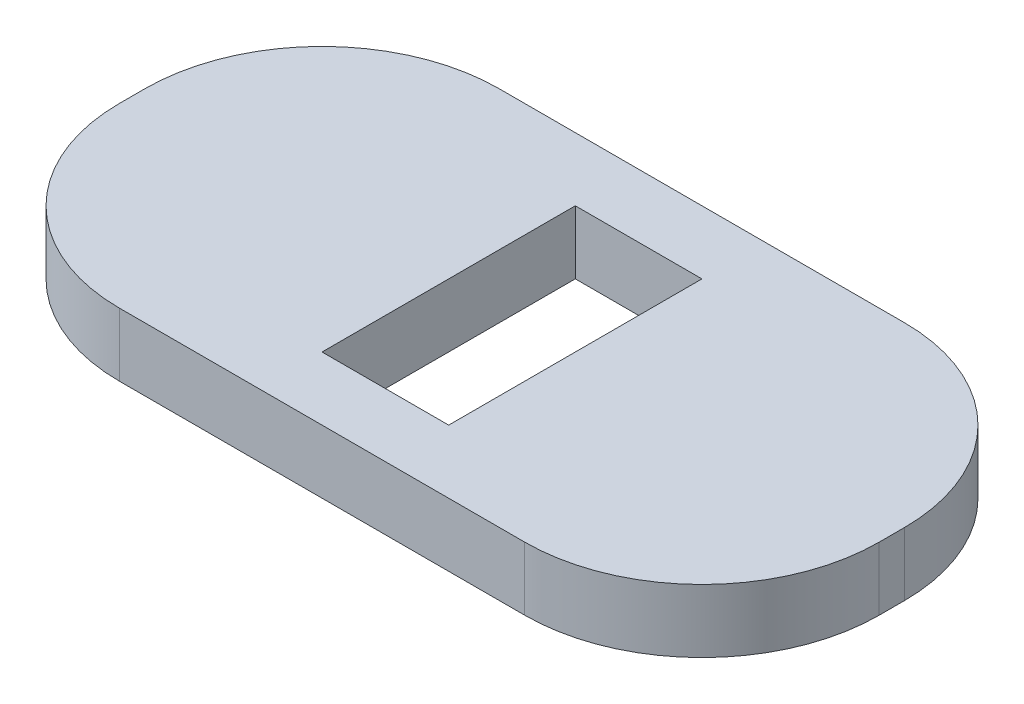
SolidWorks part; units mm, degrees
ref_plane "Front Plane" through (0, 0, 0) normal (0, 0, 1) x (1, 0, 0)
ref_plane "Top Plane" through (0, 0, 0) normal (0, 1, 0) x (1, 0, 0)
ref_plane "Right Plane" through (0, 0, 0) normal (1, 0, 0) x (0, 0, -1)
sketch "Sketch1" plane through (0, 0, 0) normal (0, 1, 0) x (1, 0, 0)
  line L0 (38.1, 38.1) -> (38.1, 0) construction
  line L1 (17.78, 0) -> (58.42, 0)
  line L2 (0, 17.78) -> (0, 20.32)
  line L3 (17.78, 38.1) -> (58.42, 38.1)
  line L4 (76.2, 17.78) -> (76.2, 20.32)
  line L5 (10.033, 19.05) -> (66.167, 19.05) construction
  line L7 (31.75, 6.35) -> (44.45, 6.35)
  line L9 (31.75, 6.35) -> (31.75, 31.75)
  line L10 (31.75, 31.75) -> (44.45, 31.75)
  line L11 (44.45, 6.35) -> (44.45, 31.75)
  line L12 (31.75, 6.35) -> (44.45, 31.75) construction
  line L13 (31.75, 31.75) -> (44.45, 6.35) construction
  arc A0 (58.42, 0) -> (76.2, 17.78) centre (58.42, 17.78) ccw
  arc A1 (58.42, 38.1) -> (76.2, 20.32) centre (58.42, 20.32) cw
  arc A2 (17.78, 0) -> (0, 17.78) centre (17.78, 17.78) cw
  arc A3 (0, 20.32) -> (17.78, 38.1) centre (17.78, 20.32) cw
  point P9 (38.1, 19.05)
  point P10 (10.033, 19.05)
  point P11 (38.1, 19.05)
  point P18 (76.2, 0)
  point P19 (38.1, 19.05)
  point P24 (0, 0)
  point P27 (0, 38.1)
  dimension "D6" = 17.78
  dimension "D1" = 76.2
  dimension "D2" = 38.1
  dimension "D3" = 56.134
  dimension "D4" = 12.7
  dimension "D5" = 25.4
extrude "Boss-Extrude1" add sketch "Sketch1" along normal blind 6.35
